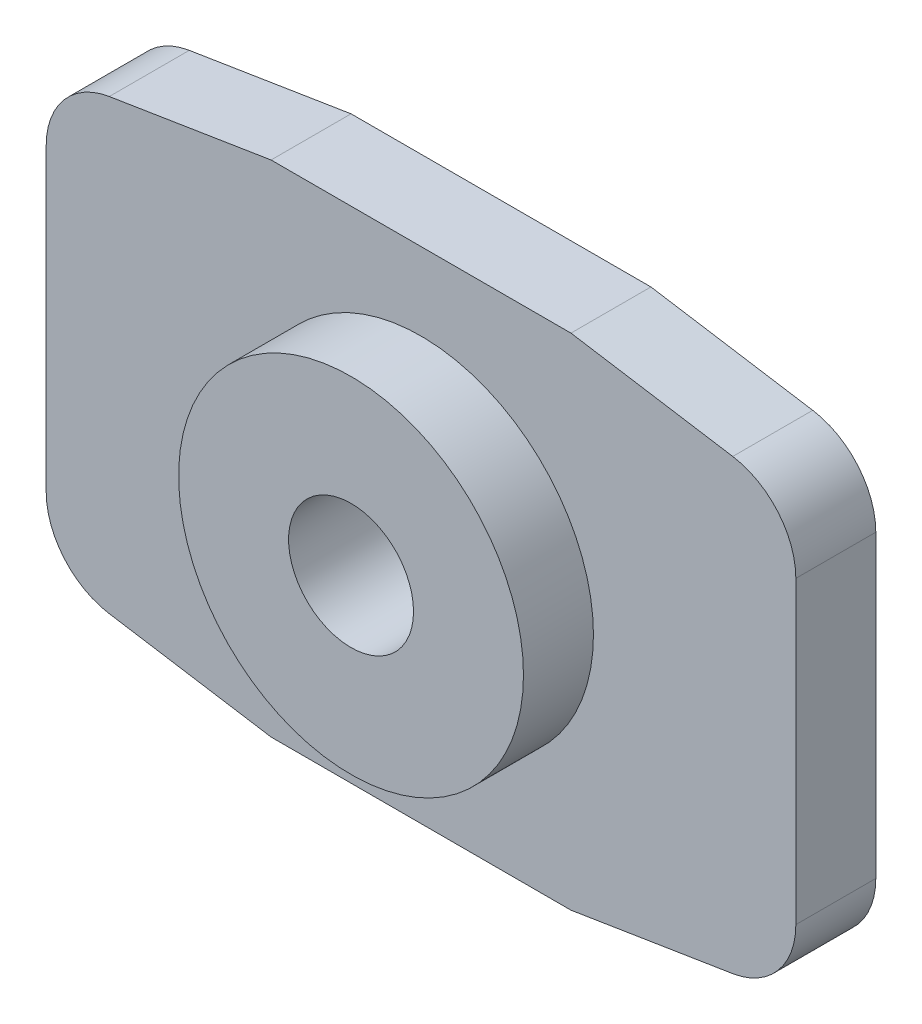
SolidWorks part; units mm, degrees
material "Plain Carbon Steel"
ref_plane "Front Plane" through (0, 0, 0) normal (0, 0, 1) x (1, 0, 0)
ref_plane "Top Plane" through (0, 0, 0) normal (0, 1, 0) x (1, 0, 0)
ref_plane "Right Plane" through (0, 0, 0) normal (1, 0, 0) x (0, 0, -1)
sketch "Sketch1" plane through (0, 0, 0) normal (0, 0, 1) x (1, 0, 0)
  line L0 (-7.5, 0) -> (7.5, 0) construction
  line L1 (-6.2374, 4.4811) -> (-3, 5)
  line L2 (-7.5, -3) -> (-7.5, 3)
  line L3 (-3, 5) -> (3, 5)
  line L4 (7.5, -3) -> (7.5, 3)
  line L5 (0, 5) -> (0, 0) construction
  line L6 (6.2374, 4.4811) -> (3, 5)
  line L7 (6.2374, -4.4811) -> (3, -5)
  line L8 (-3, -5) -> (3, -5)
  line L9 (-6.2374, -4.4811) -> (-3, -5)
  arc A0 (7.5, 3) -> (6.2374, 4.4811) centre (6, 3) ccw
  arc A1 (-7.5, -3) -> (-6.2374, -4.4811) centre (-6, -3) ccw
  arc A2 (7.5, -3) -> (6.2374, -4.4811) centre (6, -3) cw
  arc A3 (-7.5, 3) -> (-6.2374, 4.4811) centre (-6, 3) cw
  dimension "D3" = 6
  dimension "D5" = 1.5
  dimension "D1" = 15
  dimension "D2" = 10
  dimension "D4" = 6
extrude "Boss-Extrude1" add sketch "Sketch1" along normal blind 1.6
sketch "Sketch2" plane through (0, 0, 1.6) normal (0, 0, 1) x (1, 0, 0)
  line L0 (-7.5, 0) -> (0, 0) construction
  line L1 (-7.5, 3) -> (-7.5, -3) construction
  line L2 (0, 0) -> (0, 5) construction
  line L4 (3, 5) -> (-3, 5) construction
  circle A0 centre (0, 0) radius 3.45
  dimension "D2" = 6.9
extrude "Boss-Extrude2" add sketch "Sketch2" along normal blind 1.4
hole_wizard "M3x0.5 Tapped Hole1" positions "Sketch4" profile "Sketch3" tap size "M3x0.5" standard "ANSI Metric" end condition through all
sketch "Sketch4" plane through (0, 0, 3) normal (0, 0, 1) x (1, 0, 0)
  point P0 (0, 0)
sketch "Sketch3" plane through (0, 0, 3) normal (1, 0, 0) x (0, -1, 0)
  line L0 (0, 0) -> (0, 3)
  line L1 (0, 3) -> (1.25, 3)
  line L2 (1.25, 3) -> (1.25, 0)
  line L5 (1.25, 0) -> (0, 0)
  line L11 (0, -6.35) -> (0, 107.95) construction
  dimension "Thru Tap Drill Dia." = 2.5
  dimension "Thru Tap Drill Depth" = 3
